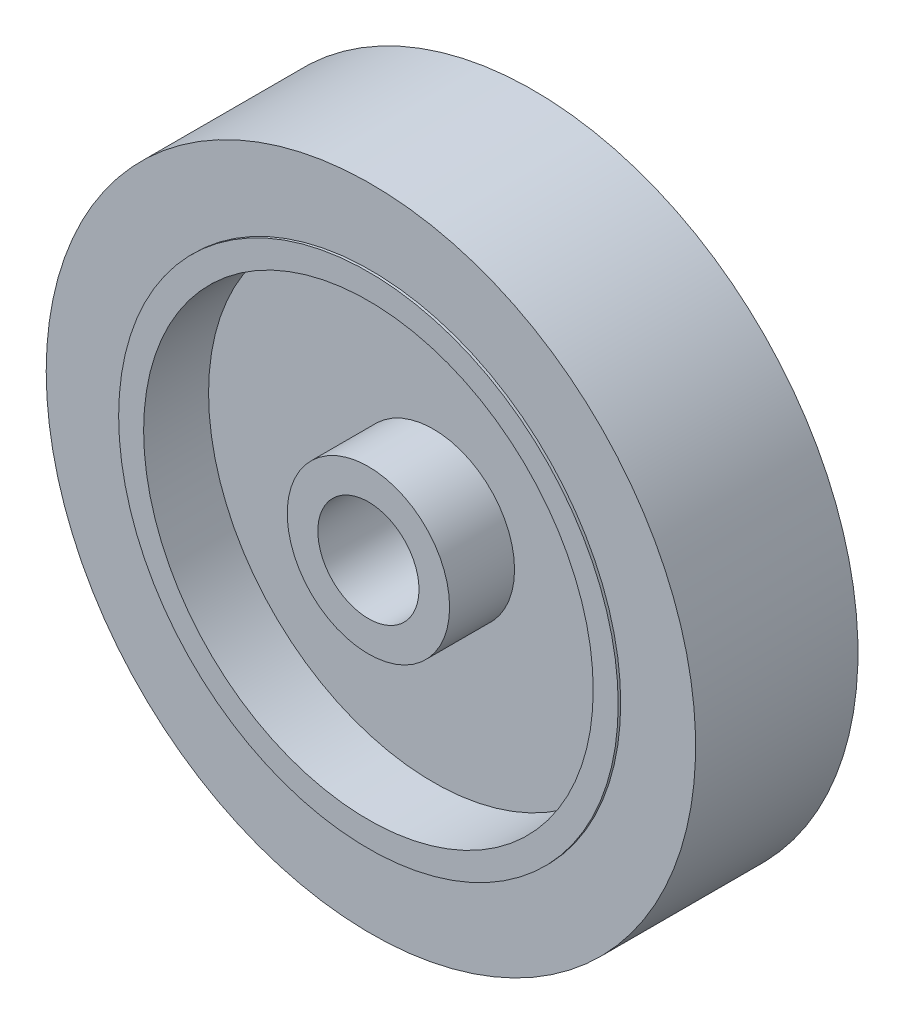
SolidWorks part; units mm, degrees
ref_plane "Alzado" through (0, 0, 0) normal (0, 0, 1) x (1, 0, 0)
ref_plane "Planta" through (0, 0, 0) normal (0, 1, 0) x (1, 0, 0)
ref_plane "Vista lateral" through (0, 0, 0) normal (1, 0, 0) x (0, 0, -1)
sketch "Croquis1" plane through (0, 0, 0) normal (0, 0, 1) x (1, 0, 0)
  circle A0 centre (0, 0) radius 26
extrude "Saliente-Extruir1" add sketch "Croquis1" along normal mid plane 13
sketch "Croquis2" plane through (0, 0, 6.5) normal (0, 0, 1) x (1, 0, 0)
  circle A0 centre (0, 0) radius 20
  circle A1 centre (0, 0) radius 18
  dimension "D1" = 40
  dimension "D2" = 36
extrude "Saliente-Extruir3" add sketch "Croquis2" along normal blind 0.2
sketch "Croquis4" plane through (0, 0, -6.5) normal (0, 0, -1) x (-1, 0, 0)
  circle A0 centre (0, 0) radius 20
  circle A1 centre (0, 0) radius 18
  dimension "D1" = 40
  dimension "D2" = 36
extrude "Saliente-Extruir4" add sketch "Croquis4" along normal blind 0.2
sketch "Croquis5" plane through (0, 0, -6.5) normal (0, 0, -1) x (-1, 0, 0)
  circle A0 centre (0, 0) radius 18
extrude "Cortar-Extruir1" cut sketch "Croquis5" against normal blind 5
sketch "Croquis6" plane through (0, 0, 6.5) normal (0, 0, 1) x (1, 0, 0)
  circle A0 centre (0, 0) radius 18
extrude "Cortar-Extruir2" cut sketch "Croquis6" against normal blind 5
sketch "Croquis7" plane through (0, 0, -1.5) normal (0, 0, -1) x (-1, 0, 0)
  circle A0 centre (0, 0) radius 6.5
  circle A1 centre (0, 0) radius 4.05
  dimension "D1" = 13
extrude "Saliente-Extruir5" add sketch "Croquis7" along normal up to surface and the other way up to surface up to face at (-20, 0, -6.7) other way up to face at (20, 0, 6.7)
sketch "Croquis8" plane through (0, 0, -1.5) normal (0, 0, -1) x (-1, 0, 0)
  circle A0 centre (0, 0) radius 4.05
  dimension "D1" = 8.1
extrude "Cortar-Extruir3" cut sketch "Croquis8" against normal mid plane 78
